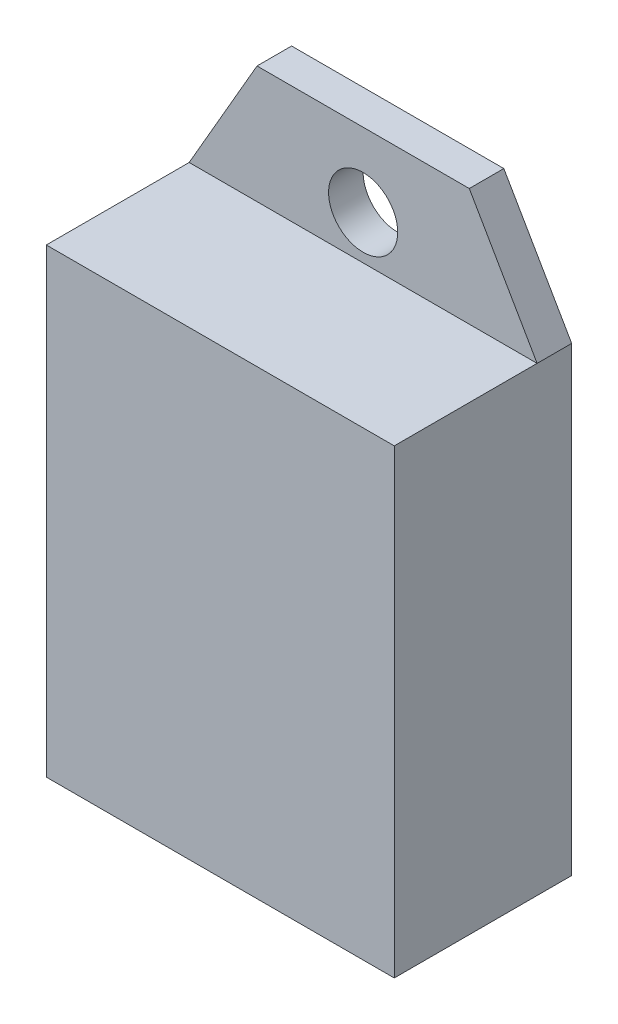
SolidWorks part; units mm, degrees
ref_plane "Front Plane" through (0, 0, 0) normal (0, 0, 1) x (1, 0, 0)
ref_plane "Top Plane" through (0, 0, 0) normal (0, 1, 0) x (1, 0, 0)
ref_plane "Right Plane" through (0, 0, 0) normal (1, 0, 0) x (0, 0, -1)
sketch "Sketch1" plane through (0, 0, 0) normal (0, 0, 1) x (1, 0, 0)
  line L1 (-7.55, -10) -> (7.55, -10)
  line L2 (-7.55, -10) -> (-7.55, 10)
  line L3 (-7.55, 10) -> (7.55, 10)
  line L4 (7.55, -10) -> (7.55, 10)
  line L5 (-7.55, -10) -> (7.55, 10) construction
  line L6 (-7.55, 10) -> (7.55, -10) construction
  point P0 (0, 0)
  dimension "D1" = 20
  dimension "D2" = 15.1
extrude "Boss-Extrude1" add sketch "Sketch1" along normal blind 7.7
sketch "Sketch3" plane through (0, 0, 0) normal (0, 0, -1) x (-1, 0, 0)
  line L0 (0, 0) -> (0, 50000) construction
  line L1 (-7.55, 10) -> (7.55, 10) construction
  line L2 (4.6055, 15.1) -> (-4.6055, 15.1)
  line L3 (-4.6055, 15.1) -> (-7.55, 10)
  line L4 (7.55, -10) -> (-7.55, -10) construction
  line L5 (4.6055, 15.1) -> (7.55, 10)
  line L6 (7.55, 10) -> (-7.55, 10)
  point P5 (0, 10)
  point P14 (0, 15.1)
  dimension "D1" = 25.1
  dimension "D2" = 60
extrude "Boss-Extrude2" add sketch "Sketch3" against normal blind 1.5
sketch "Sketch4" plane through (0, 0, 1.5) normal (0, 0, 1) x (1, 0, 0)
  line L0 (0, 10) -> (0, 15.1) construction
  line L1 (7.55, 10) -> (-7.55, 10) construction
  line L2 (-4.6055, 15.1) -> (4.6055, 15.1) construction
  circle A0 centre (0, 11.9) radius 1.5
  dimension "D1" = 3
  dimension "D2" = 3.2
extrude "Cut-Extrude1" cut sketch "Sketch4" against normal through all
